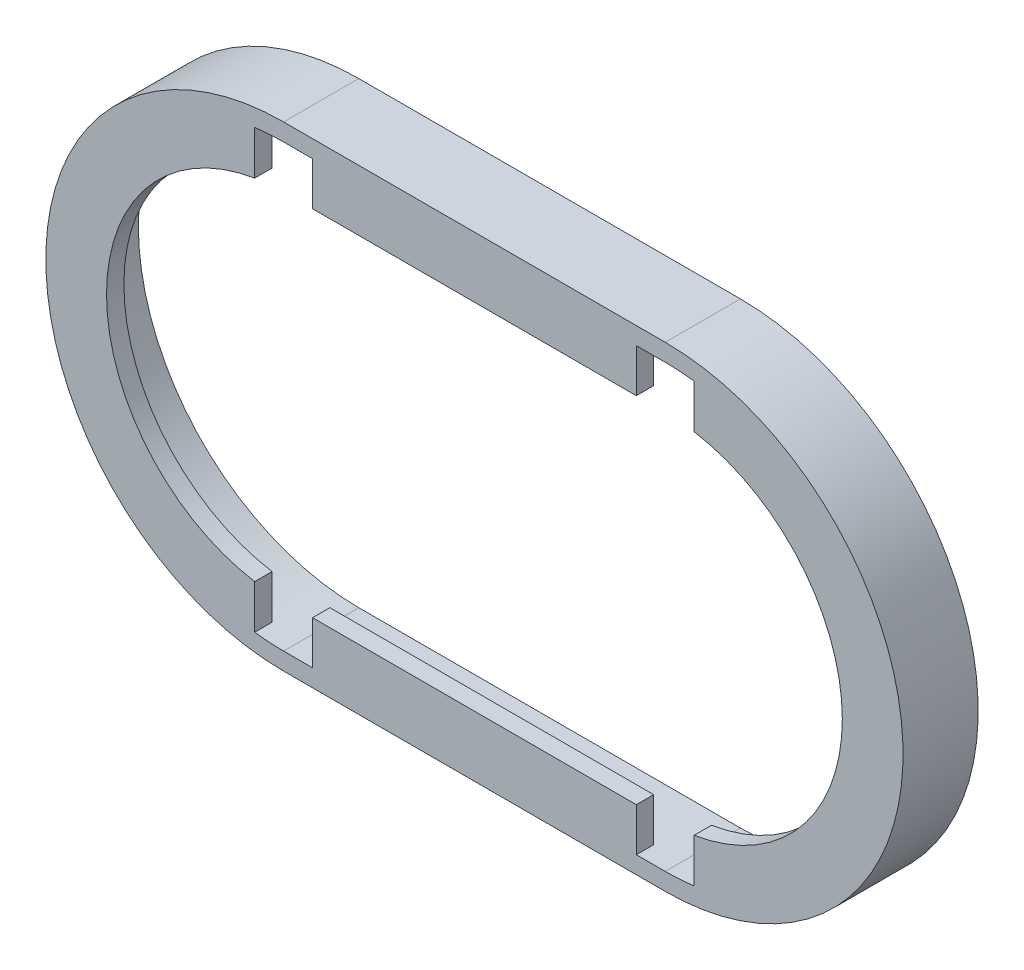
SolidWorks part; units mm, degrees
ref_plane "Front Plane" through (0, 0, 0) normal (0, 0, 1) x (1, 0, 0)
ref_plane "Top Plane" through (0, 0, 0) normal (0, 1, 0) x (1, 0, 0)
ref_plane "Right Plane" through (0, 0, 0) normal (1, 0, 0) x (0, 0, -1)
sketch "Sketch1" plane through (0, 0, 0) normal (0, 0, 1) x (1, 0, 0)
  line L0 (-34.3844, 18.7192) -> (-7.9844, 18.7192)
  line L1 (-7.9844, -11.7808) -> (-34.3844, -11.7808)
  line L2 (-34.3844, 19.9192) -> (-7.9844, 19.9192)
  line L3 (-7.9844, -12.9808) -> (-34.3844, -12.9808)
  arc A0 (-34.3844, 18.7192) -> (-34.3844, -11.7808) centre (-34.3844, 3.4692) ccw
  arc A1 (-7.9844, -11.7808) -> (-7.9844, 18.7192) centre (-7.9844, 3.4692) ccw
  arc A2 (-7.9844, -12.9808) -> (-7.9844, 19.9192) centre (-7.9844, 3.4692) ccw
  arc A3 (-34.3844, 19.9192) -> (-34.3844, -12.9808) centre (-34.3844, 3.4692) ccw
  dimension "D1" = 1.2
extrude "Boss-Extrude1" add sketch "Sketch1" along normal blind 1.2 and the other way blind 4
sketch "Sketch3" plane through (0, 0, 0) normal (0, 0, 1) x (1, 0, 0)
  line L0 (-7.9844, 18.7192) -> (-34.3844, 18.7192)
  line L1 (-7.9844, -11.7808) -> (-34.3844, -11.7808)
  line L2 (-7.9844, 15.7192) -> (-34.3844, 15.7192)
  line L3 (-7.9844, -8.7808) -> (-34.3844, -8.7808)
  line L4 (-34.3844, 18.7192) -> (-34.3844, -11.7808) construction
  line L5 (-7.9844, 18.7192) -> (-7.9844, -11.7808) construction
  line L6 (-36.3844, 18.7192) -> (-36.3844, -11.7808)
  line L7 (-32.3844, 18.7192) -> (-32.3844, -11.7808)
  line L8 (-9.9844, 18.7192) -> (-9.9844, -11.7808)
  line L9 (-5.9844, 18.7192) -> (-5.9844, -11.7808)
  arc A0 (-34.3844, 18.7192) -> (-34.3844, -11.7808) centre (-34.3844, 3.4692) ccw
  arc A1 (-7.9844, -11.7808) -> (-7.9844, 18.7192) centre (-7.9844, 3.4692) ccw
  arc A2 (-7.9844, -8.7808) -> (-7.9844, 15.7192) centre (-7.9844, 3.4692) ccw
  arc A3 (-34.3844, 15.7192) -> (-34.3844, -8.7808) centre (-34.3844, 3.4692) ccw
  arc M3 (-7.9844, 17.2192) -> (3.1987, 11.4692) centre (-7.9844, 3.4692) cw
  line M4 (3.1987, 11.4692) -> (4.9987, 11.4692)
  arc M5 (4.9987, 11.4692) -> (-7.9844, 18.7192) centre (-7.9844, 3.4692) ccw
  arc M7 (-34.3844, 18.7192) -> (-34.3844, -11.7808) centre (-34.3844, 3.4692) ccw
  arc M9 (-7.9844, -11.7808) -> (4.9987, -4.5308) centre (-7.9844, 3.4692) ccw
  line M10 (4.9987, -4.5308) -> (3.1987, -4.5308)
  arc M11 (3.1987, -4.5308) -> (-7.9844, -10.2808) centre (-7.9844, 3.4692) cw
  line M12 (-7.9844, -10.2808) -> (-34.3844, -10.2808)
  arc M13 (-34.3844, -10.2808) -> (-34.3844, 17.2192) centre (-34.3844, 3.4692) cw
  line M14 (-34.3844, 17.2192) -> (-7.9844, 17.2192)
  dimension "D2" = 26.4
  dimension "D1" = 3
  dimension "D3" = 2
  dimension "D4" = 2
  dimension "D5" = 2
  dimension "D6" = 2
extrude "Boss-Extrude2" add sketch "Sketch3" along normal up to surface (1.2 mm away) contours L6 M7 M13 | A3 L6 M13 | L8 L0 L7 M14 | L8 L7 L2 M14 | L9 M5 M3 M4 | A2 L9 A1 M11 M10 M4 M3 | L9 M11 M9 M10 | L8 L3 L7 M12 | L8 L7 L1 M12 up to face at (-21.1844, 3.4692, 1.2)
